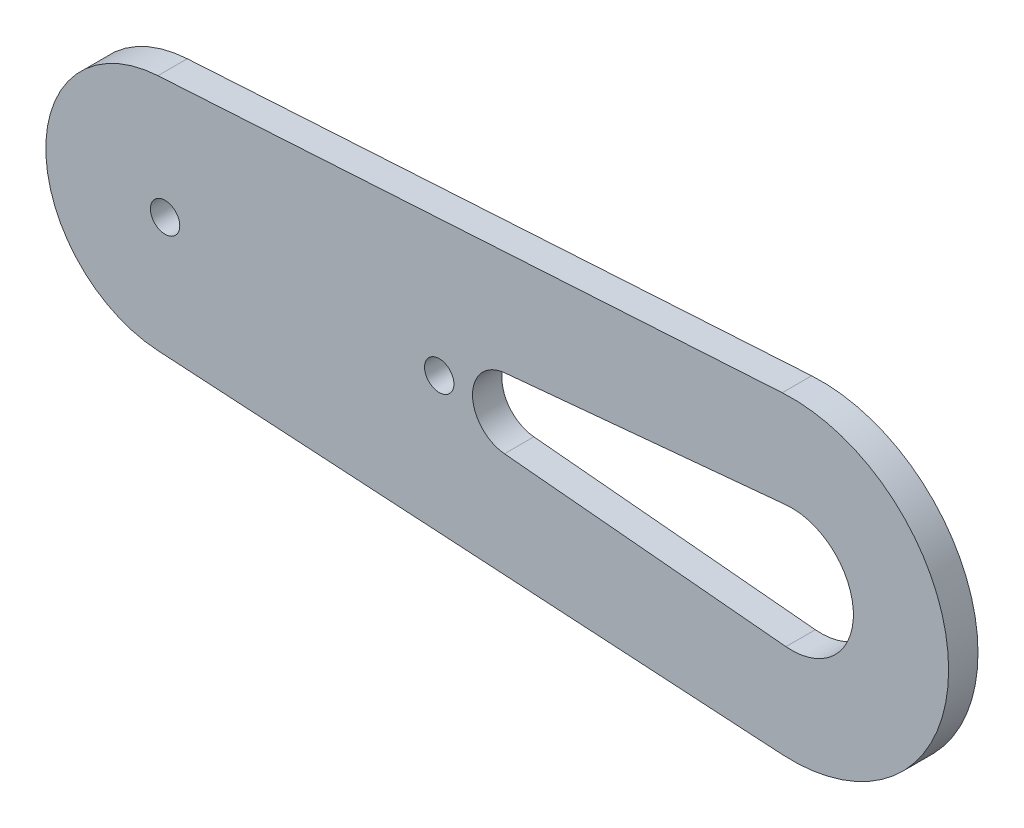
SolidWorks part; units mm, degrees
ref_plane "Front Plane" through (0, 0, 0) normal (0, 0, 1) x (1, 0, 0)
ref_plane "Top Plane" through (0, 0, 0) normal (0, 1, 0) x (1, 0, 0)
ref_plane "Right Plane" through (0, 0, 0) normal (1, 0, 0) x (0, 0, -1)
sketch "Sketch1" plane through (0, 0, 0) normal (0, 0, 1) x (1, 0, 0)
  line L0 (-52.5102, -2.3133) -> (47.1285, 3.6867)
  line L1 (47.1285, -28.3133) -> (-52.5102, -22.3133)
  arc A0 (47.1285, 3.6867) -> (47.1285, -28.3133) centre (48.092, -12.3133) cw
  arc A1 (-52.5102, -22.3133) -> (-52.5102, -2.3133) centre (-51.908, -12.3133) cw
  dimension "D1" = 100
  dimension "D2" = 20
  dimension "D3" = 32
extrude "Boss-Extrude1" add sketch "Sketch1" along normal blind 3
sketch "Sketch2" plane through (0, 0, 3) normal (0, 0, 1) x (1, 0, 0)
  line L0 (18.7568, -8.7289) -> (47.5054, -6.0406)
  line L1 (47.5054, -18.5859) -> (18.7568, -15.8976)
  arc A0 (47.5054, -6.0406) -> (47.5054, -18.5859) centre (48.092, -12.3133) cw
  arc A1 (18.7568, -15.8976) -> (18.7568, -8.7289) centre (19.092, -12.3133) cw
  arc A2 (47.1285, -28.3133) -> (47.1285, 3.6867) centre (48.092, -12.3133) ccw construction
  circle A4 centre (12.092, -12.3133) radius 1.5
  circle A5 centre (-15.908, -12.3133) radius 1.5
  circle A6 centre (-51.908, -12.3133) radius 1.5
  arc A7 (-52.5102, -2.3133) -> (-52.5102, -22.3133) centre (-51.908, -12.3133) ccw construction
  point P14 (15.492, -12.3133)
  point P15 (54.392, -12.3133)
  dimension "D1" = 6.3
  dimension "D3" = 3.6
  dimension "D4" = 36
  dimension "D2" = 38.9
  dimension "D5" = 36
extrude "Cut-Extrude1" cut sketch "Sketch2" against normal blind 3
sketch "Sketch3" plane through (0, 0, 0) normal (0, 0, -1) x (-1, 0, 0)
  line L0 (-47.1285, 3.6867) -> (52.5102, -2.3133) construction
  line L1 (52.5102, -22.3133) -> (-47.1285, -28.3133) construction
  line L2 (16.6403, -0.1533) -> (68.7016, -0.1533)
  line L3 (68.7016, -0.1533) -> (68.7016, -19.9326)
  line L4 (16.6403, -24.4733) -> (68.7016, -24.4733)
  line L5 (68.7016, -19.9326) -> (68.7016, -24.4733)
  arc A0 (16.6403, -0.1533) -> (16.6403, -24.4733) centre (15.908, -12.3133) cw
  point P8 (0, 0)
  point P12 (0, 0)
  point P13 (66.6349, -0.8679)
  point P14 (0, 0)
  point P15 (0, 0)
  point P16 (67.1985, -23.7587)
  point P17 (0, 0)
  point P18 (0, 0)
  point P19 (0, 0)
  point P20 (16.6403, -24.4733)
  point P21 (68.7016, -24.4733)
extrude "Cut-Extrude2" cut sketch "Sketch3" against normal blind 3
